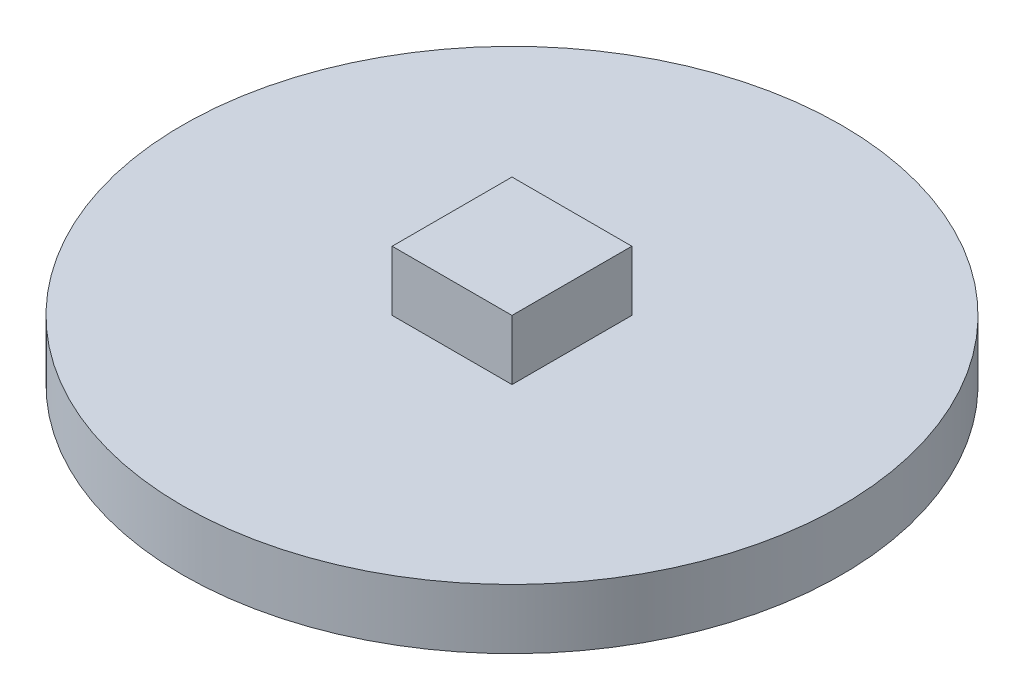
SolidWorks part; units mm, degrees
ref_plane "Front Plane" through (0, 0, 0) normal (0, 0, 1) x (1, 0, 0)
ref_plane "Top Plane" through (0, 0, 0) normal (0, 1, 0) x (1, 0, 0)
ref_plane "Right Plane" through (0, 0, 0) normal (1, 0, 0) x (0, 0, -1)
sketch "Sketch1" plane through (0, 0, 0) normal (0, 1, 0) x (1, 0, 0)
  circle A0 centre (0, 0) radius 11
  dimension "D1" = 22
extrude "Boss-Extrude1" add sketch "Sketch1" along normal blind 2
sketch "Sketch2" plane through (0, 2, 0) normal (0, 1, 0) x (1, 0, 0)
  line L1 (2, 2) -> (-2, 2)
  line L2 (2, 2) -> (2, -2)
  line L3 (2, -2) -> (-2, -2)
  line L4 (-2, 2) -> (-2, -2)
  line L5 (2, 2) -> (-2, -2) construction
  line L6 (2, -2) -> (-2, 2) construction
  point P0 (0, 0)
  dimension "D1" = 4
  dimension "D2" = 4
extrude "Boss-Extrude2" add sketch "Sketch2" along normal blind 2
